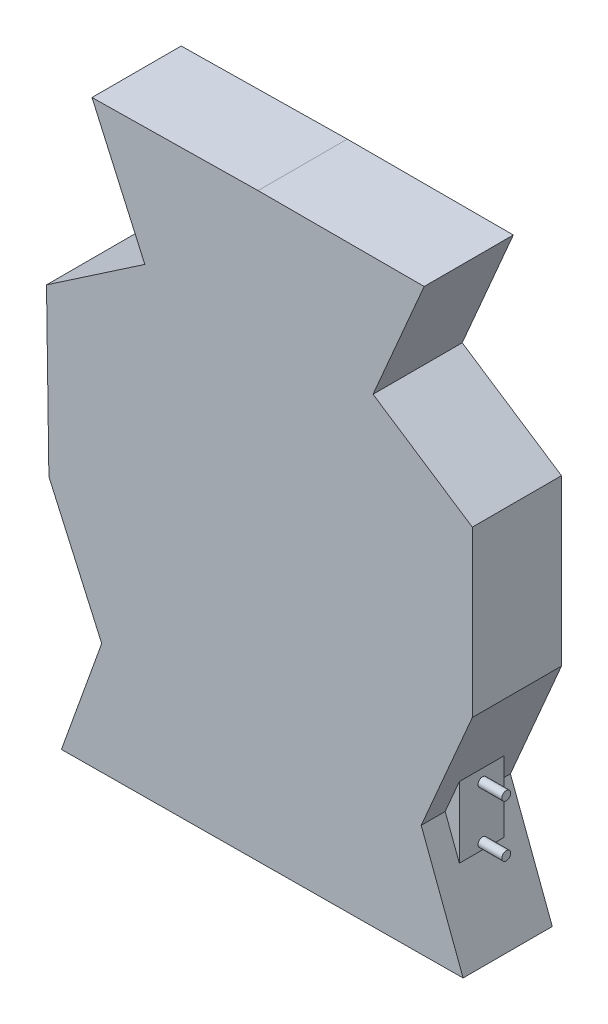
SolidWorks part; units mm, degrees
ref_plane "Front Plane" through (0, 0, 0) normal (0, 0, 1) x (1, 0, 0)
ref_plane "Top Plane" through (0, 0, 0) normal (0, 1, 0) x (1, 0, 0)
ref_plane "Right Plane" through (0, 0, 0) normal (1, 0, 0) x (0, 0, -1)
sketch "Sketch2" plane through (0, 0, 0) normal (0, 0, 1) x (1, 0, 0)
  line L16 (-35.6592, 48.9942) -> (64.2976, 48.9942) construction
  line L17 (64.2976, 48.9942) -> (64.2976, -151.0058) construction
  line L18 (64.2976, -151.0058) -> (-132.7222, -151.0058) construction
  line L23 (-132.7222, -151.0058) -> (-132.5855, 13.8223) construction
  line L28 (-35.6592, 48.9942) -> (-34.2123, -151.0058) construction
  line L29 (-132.6538, -68.5917) -> (64.2976, -68.7551) construction
  line L30 (-35.6592, 48.9942) -> (20.212, 48.9942)
  line L31 (20.212, 48.9942) -> (3.0203, 8.9942)
  line L32 (3.0203, 8.9942) -> (36.4176, -13.02)
  line L33 (36.4176, -13.02) -> (36.4176, -68.4856)
  line L34 (36.4176, -68.4856) -> (19.2259, -108.4856)
  line L35 (19.2259, -108.4856) -> (33.3181, -145.921)
  line L36 (-88.26, -109.2632) -> (-101.8092, -146.8986)
  line L37 (-106.0287, -69.5162) -> (-88.26, -109.2632)
  line L38 (-106.8312, -14.0564) -> (-106.0287, -69.5162)
  line L39 (-73.756, 8.4387) -> (-106.8312, -14.0564)
  line L40 (-91.5246, 48.1858) -> (-73.756, 8.4387)
  line L41 (-101.8092, -146.8986) -> (33.3181, -145.921)
  line L42 (-91.5246, 48.1858) -> (-35.6592, 48.9942)
  dimension "D1" = 200
  dimension "D2" = 200
  dimension "D3" = 40
  dimension "D4" = 40
  dimension "D5" = 40
  dimension "D6" = 111.7396
  dimension "D7" = 135.1273
  dimension "4" = 40
extrude "Boss-Extrude1" add sketch "Sketch2" along normal blind 30
sketch "Sketch6" plane through (0, 0, 0) normal (1, 0, 0) x (0, 0, -1)
  line L0 (-6.9415, -93.5714) -> (-21.9415, -93.5714)
  line L1 (-6.9415, -93.5714) -> (-6.9415, -123.5714)
  line L2 (-6.9415, -123.5714) -> (-21.9415, -123.5714)
  line L3 (-21.9415, -93.5714) -> (-21.9415, -123.5714)
  dimension "D1" = 6.9415
  dimension "D2" = 21.9415
  dimension "D3" = 93.5714
  dimension "D4" = 123.5714
extrude "Boss-Extrude2" add sketch "Sketch6" along normal blind 24
sketch "Sketch7" plane through (24, 0, 0) normal (1, 0, 0) x (0, 0, -1)
  circle A2 centre (-14.1637, -118.8737) radius 1.5
  circle A3 centre (-14.1637, -101.3737) radius 1.5
  dimension "D1" = 3
  dimension "D2" = 3
  dimension "D3" = 17.5
ref_plane "Plane3" through (0, 0, 15) normal (0, 0, -1) x (-1, 0, 0)
sketch "Sketch13" plane through (0, 0, 15) normal (0, 0, -1) x (-1, 0, 0)
  line L12 (92.491, -97.3776) -> (87.7169, -108.4856)
  line L13 (87.7169, -108.4856) -> (92.491, -121.1679)
  line L14 (92.491, -121.1679) -> (92.491, -97.3776)
extrude "Boss-Extrude5" add sketch "Sketch13" along normal mid plane 20
sketch "Sketch15" plane through (-92.491, 0, 0) normal (-1, 0, 0) x (0, 0, 1)
  circle A0 centre (14.1637, -101.3737) radius 1.5
  circle A1 centre (14.1637, -118.8737) radius 1.5
  dimension "D1" = 3
extrude "Boss-Extrude7" add sketch "Sketch15" along normal mid plane 16
extrude "Boss-Extrude8" add sketch "Sketch7" along normal mid plane 16
